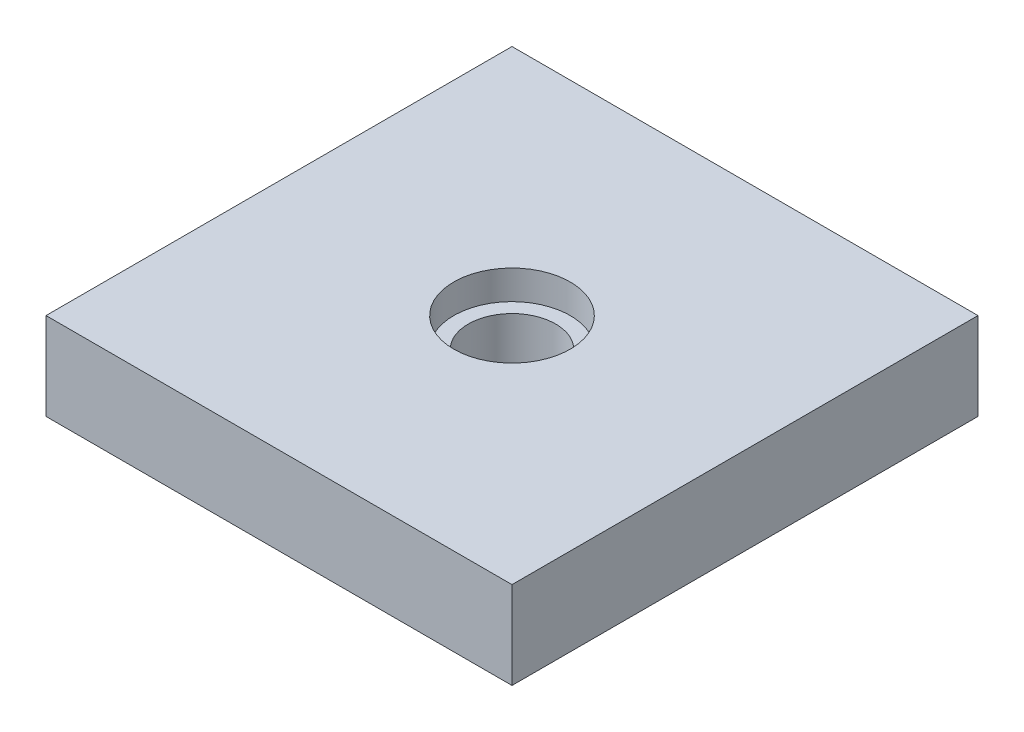
SolidWorks part; units mm, degrees
ref_plane "Front" through (0, 0, 0) normal (0, 0, 1) x (1, 0, 0)
ref_plane "Top" through (0, 0, 0) normal (0, 1, 0) x (1, 0, 0)
ref_plane "Right" through (0, 0, 0) normal (1, 0, 0) x (0, 0, -1)
sketch "Sketch1" plane through (0, 0, 0) normal (0, -1, 0) x (1, 0, 0)
  line L1 (101.6, 101.6) -> (-101.6, 101.6)
  line L2 (101.6, 101.6) -> (101.6, -101.6)
  line L3 (101.6, -101.6) -> (-101.6, -101.6)
  line L4 (-101.6, 101.6) -> (-101.6, -101.6)
  line L5 (101.6, 101.6) -> (-101.6, -101.6) construction
  line L6 (101.6, -101.6) -> (-101.6, 101.6) construction
  circle A0 centre (0, 0) radius 71.5566 construction
  circle A1 centre (0, 0) radius 82.8574 construction
  point P7 (0, 0)
  dimension "D1" = 203.2
extrude "Boss-Extrude1" add sketch "Sketch1" along normal blind 38.1
sketch "Sketch2" plane through (0, 0, 0) normal (0, 1, 0) x (1, 0, 0)
  circle A0 centre (0, 0) radius 19.05 construction
  circle A1 centre (0, 0) radius 25.4
  dimension "D1" = 38.1
  dimension "D2" = 50.8
extrude "Cut-Extrude1" cut sketch "Sketch2" against normal blind 12.7
sketch "Sketch3" plane through (0, -12.7, 0) normal (0, 1, 0) x (1, 0, 0)
  circle A0 centre (0, 0) radius 19.05
  dimension "D1" = 38.1
extrude "Cut-Extrude2" cut sketch "Sketch3" against normal through all
